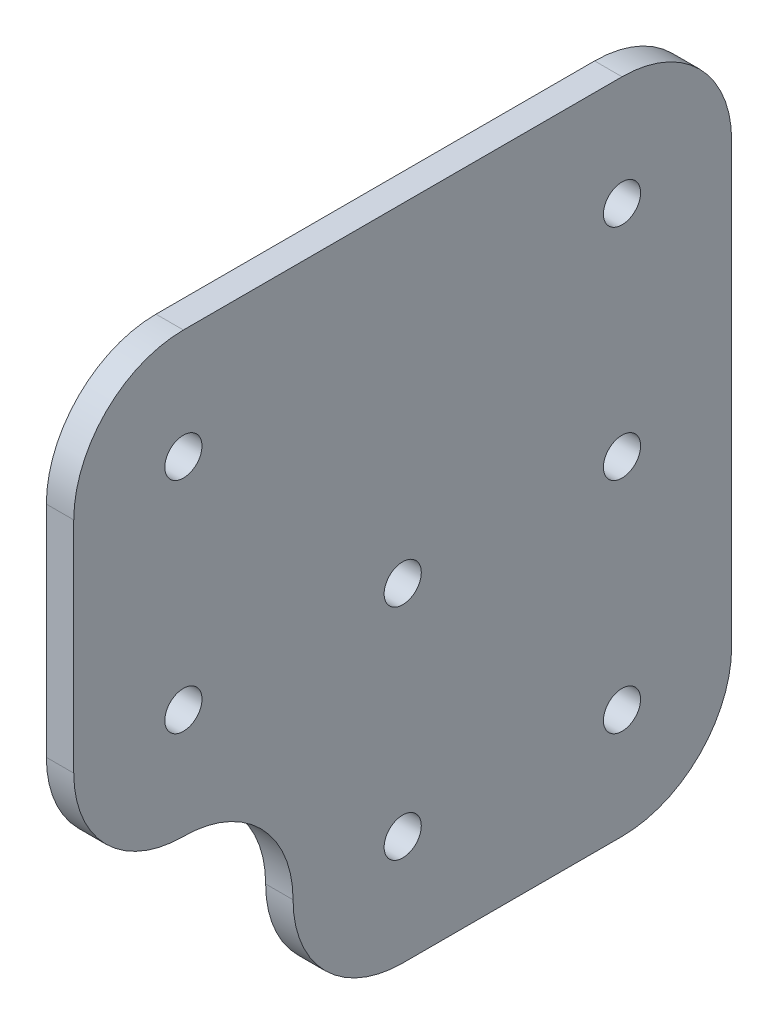
SolidWorks part; units mm, degrees
material "6061-T6 (SS)"
ref_plane "Front Plane" through (0, 0, 0) normal (0, 0, 1) x (1, 0, 0)
ref_plane "Top Plane" through (0, 0, 0) normal (0, 1, 0) x (1, 0, 0)
ref_plane "Right Plane" through (0, 0, 0) normal (1, 0, 0) x (0, 0, -1)
sketch "Sketch1" plane through (0, 0, 0) normal (1, 0, 0) x (0, 0, -1)
  line L1 (-38.1, -38.1) -> (38.1, -38.1)
  line L2 (-38.1, -38.1) -> (-38.1, 38.1)
  line L3 (-38.1, 38.1) -> (38.1, 38.1)
  line L4 (38.1, -38.1) -> (38.1, 38.1)
  line L5 (-38.1, -38.1) -> (38.1, 38.1) construction
  line L6 (-38.1, 38.1) -> (38.1, -38.1) construction
  point P0 (0, 0)
  dimension "D1" = 76.2
extrude "Boss-Extrude1" add sketch "Sketch1" along normal mid plane 3.175
hole_wizard "#8 Clearance Hole1" positions "Sketch3" profile "Sketch2" hole size "#8" standard "ANSI Inch" end condition through all
sketch "Sketch3" plane through (1.5875, 0, 0) normal (1, 0, 0) x (0, 0, -1)
  line L1 (0, -25.4) -> (25.4, -25.4) construction
  line L2 (25.4, -25.4) -> (25.4, 0) construction
  line L3 (25.4, 0) -> (25.4, 25.4) construction
  line L4 (25.4, 25.4) -> (0, 25.4) construction
  line L5 (0, 25.4) -> (-25.4, 25.4) construction
  line L6 (-25.4, 25.4) -> (-25.4, 0) construction
  line L7 (-25.4, 0) -> (0, 0) construction
  line L8 (0, 0) -> (0, -25.4) construction
  line L10 (25.4, 0) -> (0, 0) construction
  line L12 (0, 25.4) -> (0, 0) construction
  line L14 (38.1, 38.1) -> (-38.1, 38.1) construction
  line L15 (-38.1, 38.1) -> (-38.1, -38.1) construction
  point P0 (-25.4, 25.4)
  point P2 (-25.4, 0)
  point P4 (25.4, 25.4)
  point P6 (0, 0)
  point P8 (25.4, 0)
  point P10 (0, -25.4)
  point P12 (25.4, -25.4)
  dimension "D1" = 25.4
  dimension "D2" = 12.7
  dimension "D3" = 12.7
sketch "Sketch2" plane through (1.5875, 25.4, 25.4) normal (0, 1, 0) x (0, 0, -1)
  line L0 (0, 0) -> (0, 3.175)
  line L1 (0, 3.175) -> (2.1526, 3.175)
  line L2 (2.1526, 3.175) -> (2.1526, 0)
  line L5 (2.1526, 0) -> (0, 0)
  line L11 (0, -6.35) -> (0, 107.95) construction
  dimension "Thru Hole Dia." = 4.3053
  dimension "Thru Hole Depth" = 3.175
sketch "Sketch4" plane through (1.5875, 0, 0) normal (1, 0, 0) x (0, 0, -1)
  line L0 (38.1, 38.1) -> (-38.1, 38.1) construction
  line L1 (-38.1, 38.1) -> (-38.1, -38.1) construction
  line L2 (38.1, -38.1) -> (38.1, 38.1) construction
  line L3 (-38.1, -38.1) -> (38.1, -38.1) construction
  line L4 (-38.1, 0) -> (-38.1, 25.4)
  line L5 (-25.4, 38.1) -> (25.4, 38.1)
  line L6 (38.1, 25.4) -> (38.1, -25.4)
  line L7 (25.4, -38.1) -> (0, -38.1)
  line L9 (-50.8, -50.8) -> (50.8, -50.8)
  line L10 (-50.8, -50.8) -> (-50.8, 50.8)
  line L11 (-50.8, 50.8) -> (50.8, 50.8)
  line L12 (50.8, -50.8) -> (50.8, 50.8)
  line L13 (-50.8, -50.8) -> (50.8, 50.8) construction
  line L14 (-50.8, 50.8) -> (50.8, -50.8) construction
  arc A0 (-25.4, 38.1) -> (-38.1, 25.4) centre (-25.4, 25.4) ccw
  arc A1 (25.4, 38.1) -> (38.1, 25.4) centre (25.4, 25.4) cw
  arc A2 (38.1, -25.4) -> (25.4, -38.1) centre (25.4, -25.4) cw
  arc A3 (0, -38.1) -> (-12.7, -25.4) centre (0, -25.4) cw
  arc A4 (-38.1, 0) -> (-25.4, -12.7) centre (-25.4, 0) ccw
  arc A5 (-12.7, -25.4) -> (-25.4, -12.7) centre (-25.4, -25.4) ccw
  point P29 (0, 0)
  dimension "D1" = 12.7
extrude "Cut-Extrude1" cut sketch "Sketch4" against normal through all
